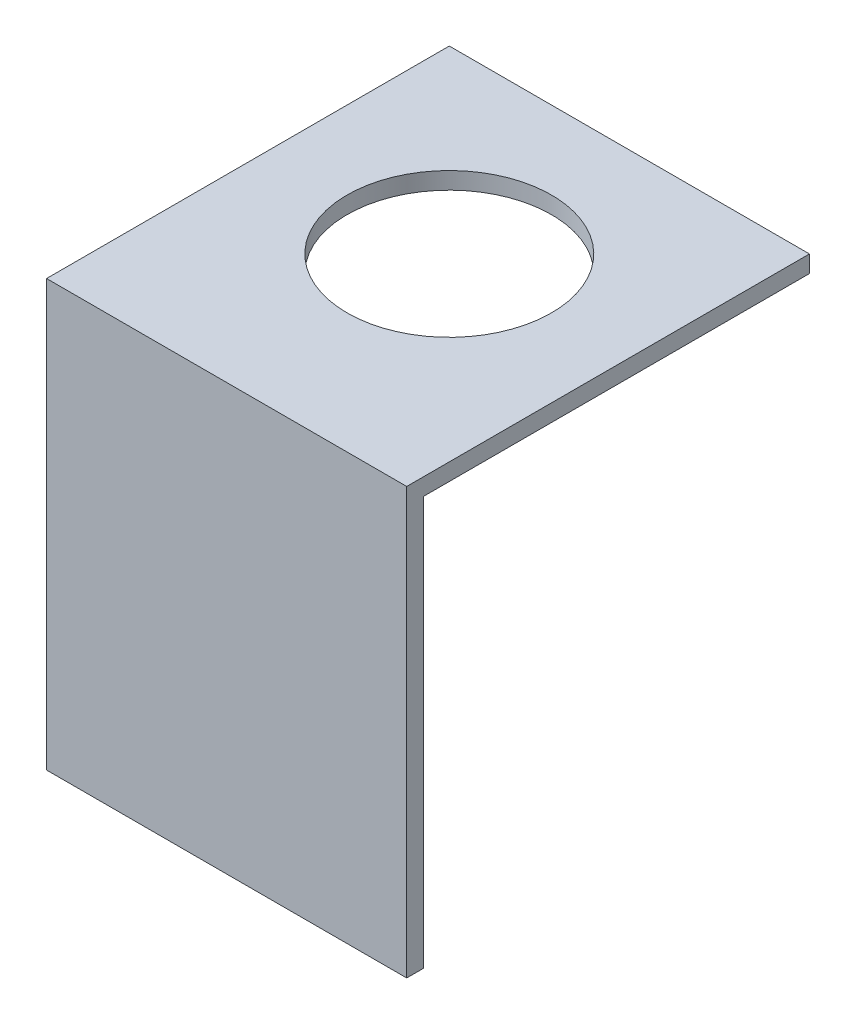
SolidWorks part; units mm, degrees
ref_plane "Ebene vorne" through (0, 0, 0) normal (0, 0, 1) x (1, 0, 0)
ref_plane "Ebene oben" through (0, 0, 0) normal (0, 1, 0) x (1, 0, 0)
ref_plane "Ebene rechts" through (0, 0, 0) normal (1, 0, 0) x (0, 0, -1)
sketch "Skizze1" plane through (0, 12.1338, 0) normal (0, 1, 0) x (1, 0, 0)
  line L0 (18.3742, -21.15) -> (-23.9258, -21.15) construction
  line L1 (-23.9258, -26.15) -> (18.3742, -26.15)
  line L2 (-23.9258, -26.15) -> (-23.9258, 21.15)
  line L3 (-23.9258, 21.15) -> (18.3742, 21.15)
  line L4 (18.3742, -26.15) -> (18.3742, 21.15)
  line L5 (-23.9258, -26.15) -> (18.3742, 21.15) construction
  line L6 (-23.9258, 21.15) -> (18.3742, -26.15) construction
  circle A0 centre (-2.7758, 0) radius 12
  circle A1 centre (-2.7758, 0) radius 11 construction
  point P0 (-2.7758, -2.5)
  dimension "D2" = 1
  dimension "D1" = 5
extrude "Aufsatz-Linear austragen1" add sketch "Skizze1" along normal blind 2
sketch "Skizze2" plane through (0, 12.1338, 0) normal (0, -1, 0) x (1, 0, 0)
  line L1 (-23.9258, 24.15) -> (18.3742, 24.15)
  line L2 (-23.9258, 24.15) -> (-23.9258, 26.15)
  line L3 (-23.9258, 26.15) -> (18.3742, 26.15)
  line L4 (18.3742, 24.15) -> (18.3742, 26.15)
  line L5 (-23.9258, 24.15) -> (18.3742, 26.15) construction
  line L6 (-23.9258, 26.15) -> (18.3742, 24.15) construction
  point P0 (-2.7758, 25.15)
  dimension "D1" = 2
extrude "Aufsatz-Linear austragen2" add sketch "Skizze2" along normal up to surface (48 mm away)
